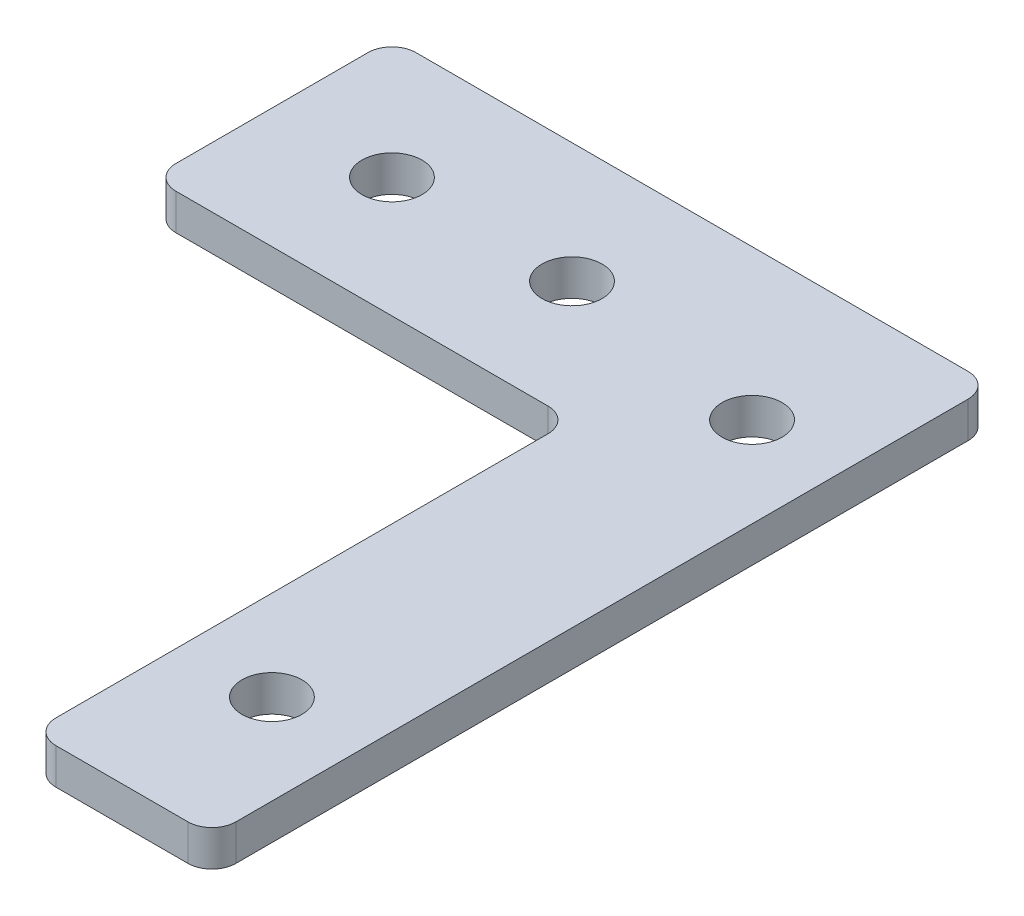
SolidWorks part; units mm, degrees
ref_plane "前视基准面" through (0, 0, 0) normal (0, 0, 1) x (1, 0, 0)
ref_plane "上视基准面" through (0, 0, 0) normal (0, 1, 0) x (1, 0, 0)
ref_plane "右视基准面" through (0, 0, 0) normal (1, 0, 0) x (0, 0, -1)
sketch "草图1" plane through (0, 0, 0) normal (0, 1, 0) x (1, 0, 0)
  line L10 (2, 0) -> (33, 0)
  line L11 (0, 2) -> (0, 18)
  line L12 (2, 20) -> (48, 20)
  line L13 (50, 0) -> (50, 18)
  line L15 (50, 0) -> (50, -43)
  line L16 (48, -45) -> (37, -45)
  line L17 (35, -2) -> (35, -43)
  circle A0 centre (42.5, 7.5) radius 2.5
  circle A1 centre (42.5, -32.5) radius 2.5
  circle A10 centre (10, 10) radius 2.5
  circle A11 centre (25, 10) radius 2.5
  arc A12 (50, 18) -> (48, 20) centre (48, 18) ccw
  arc A13 (48, -45) -> (50, -43) centre (48, -43) ccw
  arc A14 (35, -43) -> (37, -45) centre (37, -43) ccw
  arc A15 (35, -2) -> (33, 0) centre (33, -2) ccw
  arc A16 (2, 0) -> (0, 2) centre (2, 2) cw
  arc A17 (2, 20) -> (0, 18) centre (2, 18) ccw
  point P18 (50, 20)
  point P21 (50, -45)
  point P24 (35, -45)
  point P29 (0, 0)
  point P32 (0, 20)
  dimension "D6" = 15
  dimension "D9" = 5
  dimension "D14" = 5
  dimension "D10" = 2
  dimension "D2" = 50
  dimension "D3" = 20
  dimension "D4" = 10
  dimension "D5" = 45
  dimension "D7" = 12.5
  dimension "D8" = 12.5
  dimension "D18" = 15
extrude "凸台-拉伸1" add sketch "草图1" along normal blind 3
